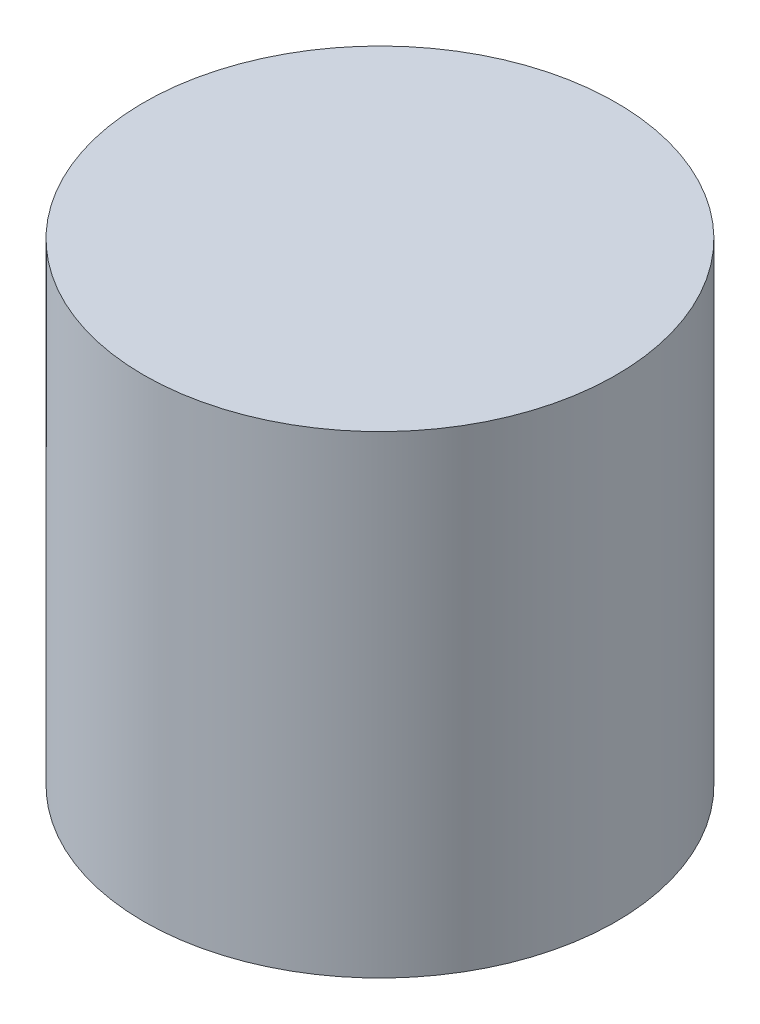
SolidWorks part; units mm, degrees
ref_plane "前视基准面" through (0, 0, 0) normal (0, 0, 1) x (1, 0, 0)
ref_plane "上视基准面" through (0, 0, 0) normal (0, 1, 0) x (1, 0, 0)
ref_plane "右视基准面" through (0, 0, 0) normal (1, 0, 0) x (0, 0, -1)
other "Configuration Table"
sketch "草图1" plane through (0, 0, 0) normal (0, 1, 0) x (1, 0, 0)
  circle A0 centre (0, 0) radius 4.99
  dimension "D1" = 9.98
extrude "凸台-拉伸2" add sketch "草图1" along normal blind 10
